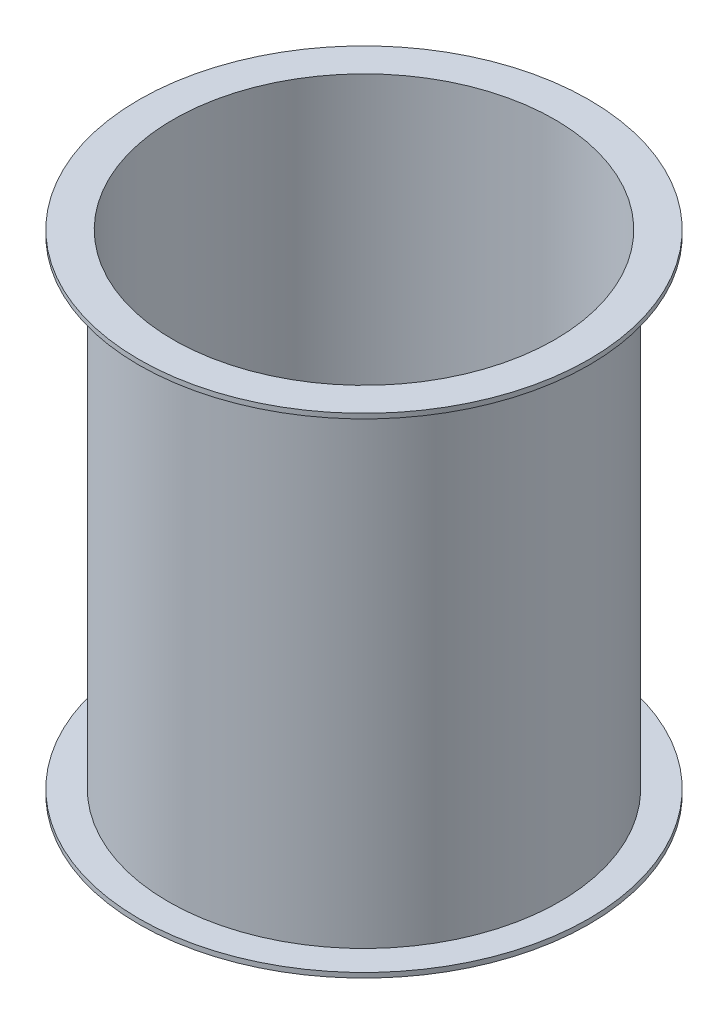
SolidWorks part; units mm, degrees
material "AISI 304"
ref_plane "Piano frontale" through (0, 0, 0) normal (0, 0, 1) x (1, 0, 0)
ref_plane "Piano superiore" through (0, 0, 0) normal (0, 1, 0) x (1, 0, 0)
ref_plane "Piano destro" through (0, 0, 0) normal (1, 0, 0) x (0, 0, -1)
sketch "Schizzo1" plane through (0, 0, 0) normal (0, 1, 0) x (1, 0, 0)
  circle A0 centre (0, 0) radius 40
extrude "Estrusione-Sottile1" add sketch "Schizzo1" along normal blind 100 thin thin type one direction reverse wall 1
sketch "Schizzo2" plane through (0, 100, 0) normal (0, 1, 0) x (1, 0, 0)
  circle A0 centre (0, 0) radius 40 construction
  circle A1 centre (0, 0) radius 40
  circle A2 centre (0, 0) radius 46
  dimension "D1" = 6
extrude "Estrusione-Estrusione1" add sketch "Schizzo2" against normal blind 1
sketch "Schizzo3" plane through (0, 0, 0) normal (0, -1, 0) x (1, 0, 0)
  circle A0 centre (0, 0) radius 40 construction
  circle A1 centre (0, 0) radius 40
  circle A2 centre (0, 0) radius 46
  dimension "D1" = 6
extrude "Estrusione-Estrusione2" add sketch "Schizzo3" against normal blind 1
sketch "Schizzo4" plane through (0, 0, 0) normal (0, -1, 0) x (1, 0, 0)
  circle A0 centre (0, 0) radius 42 construction
